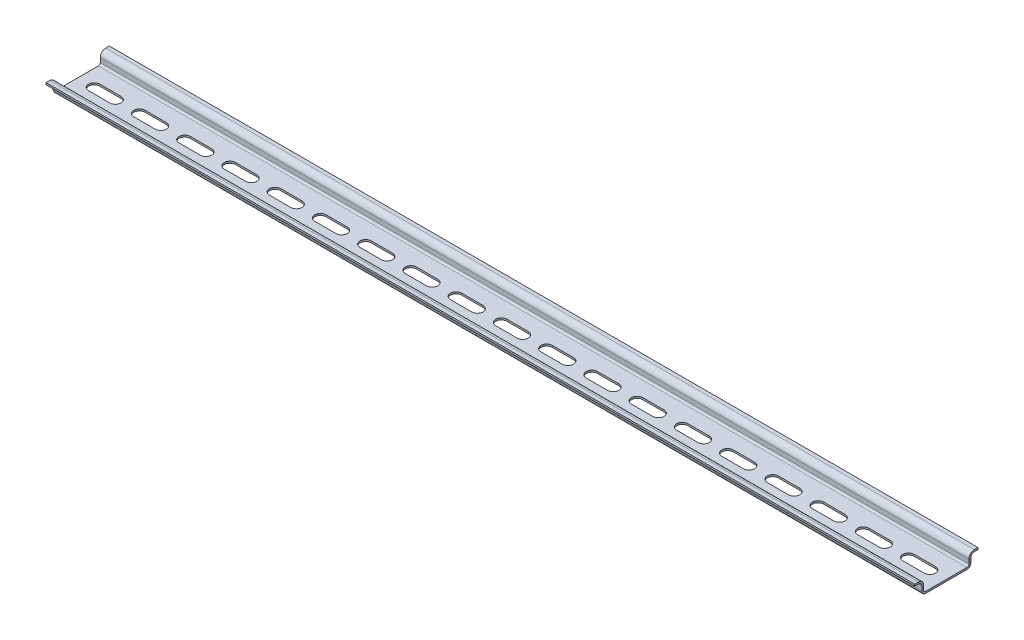
SolidWorks part; units mm, degrees
ref_plane "Front Plane" through (0, 0, 0) normal (0, 0, 1) x (1, 0, 0)
ref_plane "Top Plane" through (0, 0, 0) normal (0, 1, 0) x (1, 0, 0)
ref_plane "Right Plane" through (0, 0, 0) normal (1, 0, 0) x (0, 0, -1)
sketch "Sketch1" plane through (0, 0, 0) normal (1, 0, 0) x (0, 0, -1)
  line L0 (0, 0) -> (0, 18.2344) construction
  line L1 (0, 0) -> (26.621, 0) construction
  line L2 (-11.5, 0) -> (11.5, 0)
  line L3 (13.5, 2) -> (13.5, 4.5)
  line L4 (15.5, 6.5) -> (17.5, 6.5)
  line L5 (-13.5, 2) -> (-13.5, 4.5)
  line L6 (-15.5, 6.5) -> (-17.5, 6.5)
  arc A0 (13.5, 2) -> (11.5, 0) centre (11.5, 2) cw
  arc A1 (15.5, 6.5) -> (13.5, 4.5) centre (15.5, 4.5) ccw
  arc A2 (-13.5, 2) -> (-11.5, 0) centre (-11.5, 2) ccw
  arc A3 (-15.5, 6.5) -> (-13.5, 4.5) centre (-15.5, 4.5) cw
  point P9 (13.5, 0)
  dimension "D1" = 2
  dimension "D3" = 2
  dimension "D2" = 6.5
  dimension "D4" = 35
  dimension "D5" = 27
extrude "Extrude-Thin1" add sketch "Sketch1" along normal blind 240 and the other way blind 240 thin thin type one direction wall 1
sketch "Sketch2" plane through (0, 0, 0) normal (0, -1, 0) x (1, 0, 0)
  line L0 (0, 6.6969) -> (0, 0) construction
  line L1 (0, 0) -> (9.9599, 0) construction
  line L2 (-5.875, 3.125) -> (5.875, 3.125)
  line L3 (-5.875, -3.125) -> (5.875, -3.125)
  arc A0 (5.875, 3.125) -> (5.875, -3.125) centre (5.875, 0) cw
  arc A1 (-5.875, 3.125) -> (-5.875, -3.125) centre (-5.875, 0) ccw
  point P6 (0, 3.125)
  point P12 (0, -3.125)
  dimension "D2" = 11.75
  dimension "D1" = 6.25
extrude "Cut-Extrude1" cut sketch "Sketch2" against normal up to next
pattern_linear "LPattern1" count 10 spacing 25 along (1, 0, 0) count 10 spacing 25 along (-1, 0, 0) of "Cut-Extrude1"
